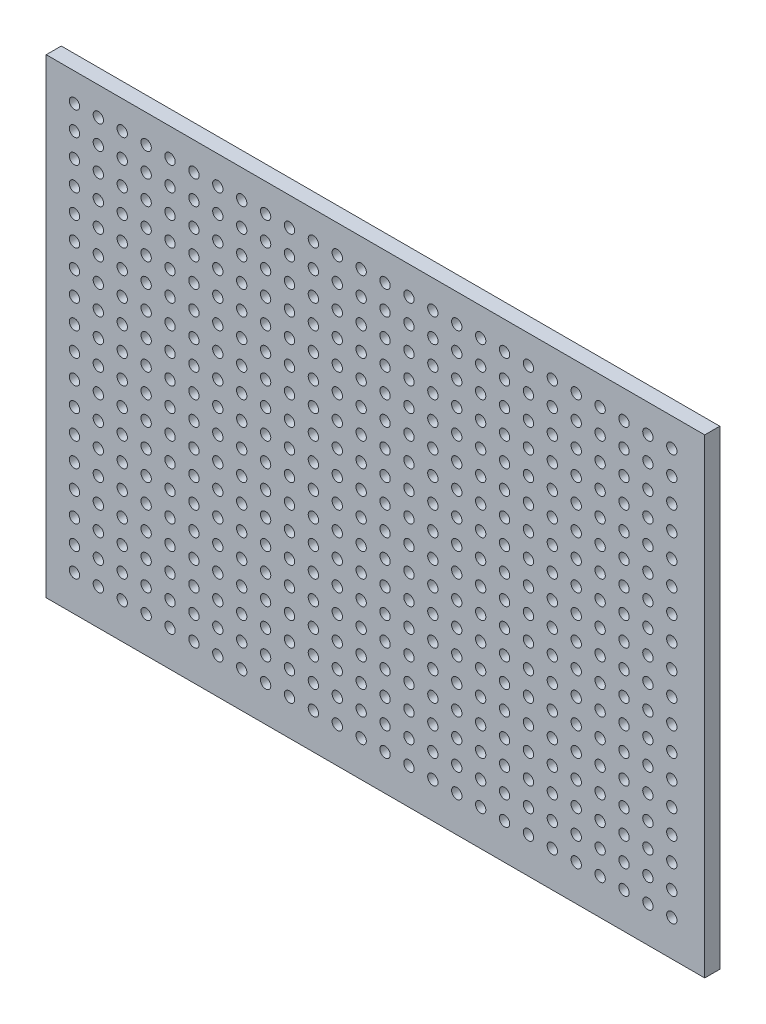
SolidWorks part; units mm, degrees
ref_plane "Front Plane" through (0, 0, 0) normal (0, 0, 1) x (1, 0, 0)
ref_plane "Top Plane" through (0, 0, 0) normal (0, 1, 0) x (1, 0, 0)
ref_plane "Right Plane" through (0, 0, 0) normal (1, 0, 0) x (0, 0, -1)
sketch "Sketch1" plane through (0, 0, 0) normal (0, 0, 1) x (1, 0, 0)
  line L1 (-35, -25) -> (35, -25)
  line L2 (-35, -25) -> (-35, 25)
  line L3 (-35, 25) -> (35, 25)
  line L4 (35, -25) -> (35, 25)
  line L5 (-35, -25) -> (35, 25) construction
  line L6 (-35, 25) -> (35, -25) construction
  point P0 (0, 0)
  dimension "D1" = 50
  dimension "D2" = 70
extrude "Boss-Extrude1" add sketch "Sketch1" along normal blind 1.6
sketch "Sketch2" plane through (0, 0, 1.6) normal (0, 0, 1) x (1, 0, 0)
  line L0 (-35, 25) -> (-35, -25) construction
  line L1 (35, 25) -> (-35, 25) construction
  line L2 (-32, 22) -> (-29.46, 22) construction
  line L3 (-32, 22) -> (-32, 19.46) construction
  circle A0 centre (-32, 22) radius 0.55
  circle A1 centre (-29.46, 22) radius 0.55
  circle A2 centre (-26.92, 22) radius 0.55
  circle A3 centre (-24.38, 22) radius 0.55
  circle A4 centre (-21.84, 22) radius 0.55
  circle A5 centre (-19.3, 22) radius 0.55
  circle A6 centre (-16.76, 22) radius 0.55
  circle A7 centre (-14.22, 22) radius 0.55
  circle A8 centre (-11.68, 22) radius 0.55
  circle A9 centre (-9.14, 22) radius 0.55
  circle A10 centre (-6.6, 22) radius 0.55
  circle A11 centre (-4.06, 22) radius 0.55
  circle A12 centre (-1.52, 22) radius 0.55
  circle A13 centre (1.02, 22) radius 0.55
  circle A14 centre (3.56, 22) radius 0.55
  circle A15 centre (6.1, 22) radius 0.55
  circle A16 centre (8.64, 22) radius 0.55
  circle A17 centre (11.18, 22) radius 0.55
  circle A18 centre (13.72, 22) radius 0.55
  circle A19 centre (16.26, 22) radius 0.55
  circle A20 centre (18.8, 22) radius 0.55
  circle A21 centre (21.34, 22) radius 0.55
  circle A22 centre (23.88, 22) radius 0.55
  circle A23 centre (26.42, 22) radius 0.55
  circle A24 centre (28.96, 22) radius 0.55
  circle A25 centre (31.5, 22) radius 0.55
  circle A26 centre (-29.46, 19.46) radius 0.55
  circle A27 centre (-26.92, 19.46) radius 0.55
  circle A28 centre (-24.38, 19.46) radius 0.55
  circle A29 centre (-21.84, 19.46) radius 0.55
  circle A30 centre (-19.3, 19.46) radius 0.55
  circle A31 centre (-16.76, 19.46) radius 0.55
  circle A32 centre (-14.22, 19.46) radius 0.55
  circle A33 centre (-11.68, 19.46) radius 0.55
  circle A34 centre (-9.14, 19.46) radius 0.55
  circle A35 centre (-6.6, 19.46) radius 0.55
  circle A36 centre (-4.06, 19.46) radius 0.55
  circle A37 centre (-1.52, 19.46) radius 0.55
  circle A38 centre (1.02, 19.46) radius 0.55
  circle A39 centre (3.56, 19.46) radius 0.55
  circle A40 centre (6.1, 19.46) radius 0.55
  circle A41 centre (8.64, 19.46) radius 0.55
  circle A42 centre (11.18, 19.46) radius 0.55
  circle A43 centre (13.72, 19.46) radius 0.55
  circle A44 centre (16.26, 19.46) radius 0.55
  circle A45 centre (18.8, 19.46) radius 0.55
  circle A46 centre (21.34, 19.46) radius 0.55
  circle A47 centre (23.88, 19.46) radius 0.55
  circle A48 centre (26.42, 19.46) radius 0.55
  circle A49 centre (28.96, 19.46) radius 0.55
  circle A50 centre (31.5, 19.46) radius 0.55
  circle A51 centre (-29.46, 16.92) radius 0.55
  circle A52 centre (-26.92, 16.92) radius 0.55
  circle A53 centre (-24.38, 16.92) radius 0.55
  circle A54 centre (-21.84, 16.92) radius 0.55
  circle A55 centre (-19.3, 16.92) radius 0.55
  circle A56 centre (-16.76, 16.92) radius 0.55
  circle A57 centre (-14.22, 16.92) radius 0.55
  circle A58 centre (-11.68, 16.92) radius 0.55
  circle A59 centre (-9.14, 16.92) radius 0.55
  circle A60 centre (-6.6, 16.92) radius 0.55
  circle A61 centre (-4.06, 16.92) radius 0.55
  circle A62 centre (-1.52, 16.92) radius 0.55
  circle A63 centre (1.02, 16.92) radius 0.55
  circle A64 centre (3.56, 16.92) radius 0.55
  circle A65 centre (6.1, 16.92) radius 0.55
  circle A66 centre (8.64, 16.92) radius 0.55
  circle A67 centre (11.18, 16.92) radius 0.55
  circle A68 centre (13.72, 16.92) radius 0.55
  circle A69 centre (16.26, 16.92) radius 0.55
  circle A70 centre (18.8, 16.92) radius 0.55
  circle A71 centre (21.34, 16.92) radius 0.55
  circle A72 centre (23.88, 16.92) radius 0.55
  circle A73 centre (26.42, 16.92) radius 0.55
  circle A74 centre (28.96, 16.92) radius 0.55
  circle A75 centre (31.5, 16.92) radius 0.55
  circle A76 centre (-29.46, 14.38) radius 0.55
  circle A77 centre (-26.92, 14.38) radius 0.55
  circle A78 centre (-24.38, 14.38) radius 0.55
  circle A79 centre (-21.84, 14.38) radius 0.55
  circle A80 centre (-19.3, 14.38) radius 0.55
  circle A81 centre (-16.76, 14.38) radius 0.55
  circle A82 centre (-14.22, 14.38) radius 0.55
  circle A83 centre (-11.68, 14.38) radius 0.55
  circle A84 centre (-9.14, 14.38) radius 0.55
  circle A85 centre (-6.6, 14.38) radius 0.55
  circle A86 centre (-4.06, 14.38) radius 0.55
  circle A87 centre (-1.52, 14.38) radius 0.55
  circle A88 centre (1.02, 14.38) radius 0.55
  circle A89 centre (3.56, 14.38) radius 0.55
  circle A90 centre (6.1, 14.38) radius 0.55
  circle A91 centre (8.64, 14.38) radius 0.55
  circle A92 centre (11.18, 14.38) radius 0.55
  circle A93 centre (13.72, 14.38) radius 0.55
  circle A94 centre (16.26, 14.38) radius 0.55
  circle A95 centre (18.8, 14.38) radius 0.55
  circle A96 centre (21.34, 14.38) radius 0.55
  circle A97 centre (23.88, 14.38) radius 0.55
  circle A98 centre (26.42, 14.38) radius 0.55
  circle A99 centre (28.96, 14.38) radius 0.55
  circle A100 centre (31.5, 14.38) radius 0.55
  circle A101 centre (-29.46, 11.84) radius 0.55
  circle A102 centre (-26.92, 11.84) radius 0.55
  circle A103 centre (-24.38, 11.84) radius 0.55
  circle A104 centre (-21.84, 11.84) radius 0.55
  circle A105 centre (-19.3, 11.84) radius 0.55
  circle A106 centre (-16.76, 11.84) radius 0.55
  circle A107 centre (-14.22, 11.84) radius 0.55
  circle A108 centre (-11.68, 11.84) radius 0.55
  circle A109 centre (-9.14, 11.84) radius 0.55
  circle A110 centre (-6.6, 11.84) radius 0.55
  circle A111 centre (-4.06, 11.84) radius 0.55
  circle A112 centre (-1.52, 11.84) radius 0.55
  circle A113 centre (1.02, 11.84) radius 0.55
  circle A114 centre (3.56, 11.84) radius 0.55
  circle A115 centre (6.1, 11.84) radius 0.55
  circle A116 centre (8.64, 11.84) radius 0.55
  circle A117 centre (11.18, 11.84) radius 0.55
  circle A118 centre (13.72, 11.84) radius 0.55
  circle A119 centre (16.26, 11.84) radius 0.55
  circle A120 centre (18.8, 11.84) radius 0.55
  circle A121 centre (21.34, 11.84) radius 0.55
  circle A122 centre (23.88, 11.84) radius 0.55
  circle A123 centre (26.42, 11.84) radius 0.55
  circle A124 centre (28.96, 11.84) radius 0.55
  circle A125 centre (31.5, 11.84) radius 0.55
  circle A126 centre (-29.46, 9.3) radius 0.55
  circle A127 centre (-26.92, 9.3) radius 0.55
  circle A128 centre (-24.38, 9.3) radius 0.55
  circle A129 centre (-21.84, 9.3) radius 0.55
  circle A130 centre (-19.3, 9.3) radius 0.55
  circle A131 centre (-16.76, 9.3) radius 0.55
  circle A132 centre (-14.22, 9.3) radius 0.55
  circle A133 centre (-11.68, 9.3) radius 0.55
  circle A134 centre (-9.14, 9.3) radius 0.55
  circle A135 centre (-6.6, 9.3) radius 0.55
  circle A136 centre (-4.06, 9.3) radius 0.55
  circle A137 centre (-1.52, 9.3) radius 0.55
  circle A138 centre (1.02, 9.3) radius 0.55
  circle A139 centre (3.56, 9.3) radius 0.55
  circle A140 centre (6.1, 9.3) radius 0.55
  circle A141 centre (8.64, 9.3) radius 0.55
  circle A142 centre (11.18, 9.3) radius 0.55
  circle A143 centre (13.72, 9.3) radius 0.55
  circle A144 centre (16.26, 9.3) radius 0.55
  circle A145 centre (18.8, 9.3) radius 0.55
  circle A146 centre (21.34, 9.3) radius 0.55
  circle A147 centre (23.88, 9.3) radius 0.55
  circle A148 centre (26.42, 9.3) radius 0.55
  circle A149 centre (28.96, 9.3) radius 0.55
  circle A150 centre (31.5, 9.3) radius 0.55
  circle A151 centre (-29.46, 6.76) radius 0.55
  circle A152 centre (-26.92, 6.76) radius 0.55
  circle A153 centre (-24.38, 6.76) radius 0.55
  circle A154 centre (-21.84, 6.76) radius 0.55
  circle A155 centre (-19.3, 6.76) radius 0.55
  circle A156 centre (-16.76, 6.76) radius 0.55
  circle A157 centre (-14.22, 6.76) radius 0.55
  circle A158 centre (-11.68, 6.76) radius 0.55
  circle A159 centre (-9.14, 6.76) radius 0.55
  circle A160 centre (-6.6, 6.76) radius 0.55
  circle A161 centre (-4.06, 6.76) radius 0.55
  circle A162 centre (-1.52, 6.76) radius 0.55
  circle A163 centre (1.02, 6.76) radius 0.55
  circle A164 centre (3.56, 6.76) radius 0.55
  circle A165 centre (6.1, 6.76) radius 0.55
  circle A166 centre (8.64, 6.76) radius 0.55
  circle A167 centre (11.18, 6.76) radius 0.55
  circle A168 centre (13.72, 6.76) radius 0.55
  circle A169 centre (16.26, 6.76) radius 0.55
  circle A170 centre (18.8, 6.76) radius 0.55
  circle A171 centre (21.34, 6.76) radius 0.55
  circle A172 centre (23.88, 6.76) radius 0.55
  circle A173 centre (26.42, 6.76) radius 0.55
  circle A174 centre (28.96, 6.76) radius 0.55
  circle A175 centre (31.5, 6.76) radius 0.55
  circle A176 centre (-29.46, 4.22) radius 0.55
  circle A177 centre (-26.92, 4.22) radius 0.55
  circle A178 centre (-24.38, 4.22) radius 0.55
  circle A179 centre (-21.84, 4.22) radius 0.55
  circle A180 centre (-19.3, 4.22) radius 0.55
  circle A181 centre (-16.76, 4.22) radius 0.55
  circle A182 centre (-14.22, 4.22) radius 0.55
  circle A183 centre (-11.68, 4.22) radius 0.55
  circle A184 centre (-9.14, 4.22) radius 0.55
  circle A185 centre (-6.6, 4.22) radius 0.55
  circle A186 centre (-4.06, 4.22) radius 0.55
  circle A187 centre (-1.52, 4.22) radius 0.55
  circle A188 centre (1.02, 4.22) radius 0.55
  circle A189 centre (3.56, 4.22) radius 0.55
  circle A190 centre (6.1, 4.22) radius 0.55
  circle A191 centre (8.64, 4.22) radius 0.55
  circle A192 centre (11.18, 4.22) radius 0.55
  circle A193 centre (13.72, 4.22) radius 0.55
  circle A194 centre (16.26, 4.22) radius 0.55
  circle A195 centre (18.8, 4.22) radius 0.55
  circle A196 centre (21.34, 4.22) radius 0.55
  circle A197 centre (23.88, 4.22) radius 0.55
  circle A198 centre (26.42, 4.22) radius 0.55
  circle A199 centre (28.96, 4.22) radius 0.55
  circle A200 centre (31.5, 4.22) radius 0.55
  circle A201 centre (-29.46, 1.68) radius 0.55
  circle A202 centre (-26.92, 1.68) radius 0.55
  circle A203 centre (-24.38, 1.68) radius 0.55
  circle A204 centre (-21.84, 1.68) radius 0.55
  circle A205 centre (-19.3, 1.68) radius 0.55
  circle A206 centre (-16.76, 1.68) radius 0.55
  circle A207 centre (-14.22, 1.68) radius 0.55
  circle A208 centre (-11.68, 1.68) radius 0.55
  circle A209 centre (-9.14, 1.68) radius 0.55
  circle A210 centre (-6.6, 1.68) radius 0.55
  circle A211 centre (-4.06, 1.68) radius 0.55
  circle A212 centre (-1.52, 1.68) radius 0.55
  circle A213 centre (1.02, 1.68) radius 0.55
  circle A214 centre (3.56, 1.68) radius 0.55
  circle A215 centre (6.1, 1.68) radius 0.55
  circle A216 centre (8.64, 1.68) radius 0.55
  circle A217 centre (11.18, 1.68) radius 0.55
  circle A218 centre (13.72, 1.68) radius 0.55
  circle A219 centre (16.26, 1.68) radius 0.55
  circle A220 centre (18.8, 1.68) radius 0.55
  circle A221 centre (21.34, 1.68) radius 0.55
  circle A222 centre (23.88, 1.68) radius 0.55
  circle A223 centre (26.42, 1.68) radius 0.55
  circle A224 centre (28.96, 1.68) radius 0.55
  circle A225 centre (31.5, 1.68) radius 0.55
  circle A226 centre (-29.46, -0.86) radius 0.55
  circle A227 centre (-26.92, -0.86) radius 0.55
  circle A228 centre (-24.38, -0.86) radius 0.55
  circle A229 centre (-21.84, -0.86) radius 0.55
  circle A230 centre (-19.3, -0.86) radius 0.55
  circle A231 centre (-16.76, -0.86) radius 0.55
  circle A232 centre (-14.22, -0.86) radius 0.55
  circle A233 centre (-11.68, -0.86) radius 0.55
  circle A234 centre (-9.14, -0.86) radius 0.55
  circle A235 centre (-6.6, -0.86) radius 0.55
  circle A236 centre (-4.06, -0.86) radius 0.55
  circle A237 centre (-1.52, -0.86) radius 0.55
  circle A238 centre (1.02, -0.86) radius 0.55
  circle A239 centre (3.56, -0.86) radius 0.55
  circle A240 centre (6.1, -0.86) radius 0.55
  circle A241 centre (8.64, -0.86) radius 0.55
  circle A242 centre (11.18, -0.86) radius 0.55
  circle A243 centre (13.72, -0.86) radius 0.55
  circle A244 centre (16.26, -0.86) radius 0.55
  circle A245 centre (18.8, -0.86) radius 0.55
  circle A246 centre (21.34, -0.86) radius 0.55
  circle A247 centre (23.88, -0.86) radius 0.55
  circle A248 centre (26.42, -0.86) radius 0.55
  circle A249 centre (28.96, -0.86) radius 0.55
  circle A250 centre (31.5, -0.86) radius 0.55
  circle A251 centre (-29.46, -3.4) radius 0.55
  circle A252 centre (-26.92, -3.4) radius 0.55
  circle A253 centre (-24.38, -3.4) radius 0.55
  circle A254 centre (-21.84, -3.4) radius 0.55
  circle A255 centre (-19.3, -3.4) radius 0.55
  circle A256 centre (-16.76, -3.4) radius 0.55
  circle A257 centre (-14.22, -3.4) radius 0.55
  circle A258 centre (-11.68, -3.4) radius 0.55
  circle A259 centre (-9.14, -3.4) radius 0.55
  circle A260 centre (-6.6, -3.4) radius 0.55
  circle A261 centre (-4.06, -3.4) radius 0.55
  circle A262 centre (-1.52, -3.4) radius 0.55
  circle A263 centre (1.02, -3.4) radius 0.55
  circle A264 centre (3.56, -3.4) radius 0.55
  circle A265 centre (6.1, -3.4) radius 0.55
  circle A266 centre (8.64, -3.4) radius 0.55
  circle A267 centre (11.18, -3.4) radius 0.55
  circle A268 centre (13.72, -3.4) radius 0.55
  circle A269 centre (16.26, -3.4) radius 0.55
  circle A270 centre (18.8, -3.4) radius 0.55
  circle A271 centre (21.34, -3.4) radius 0.55
  circle A272 centre (23.88, -3.4) radius 0.55
  circle A273 centre (26.42, -3.4) radius 0.55
  circle A274 centre (28.96, -3.4) radius 0.55
  circle A275 centre (31.5, -3.4) radius 0.55
  circle A276 centre (-29.46, -5.94) radius 0.55
  circle A277 centre (-26.92, -5.94) radius 0.55
  circle A278 centre (-24.38, -5.94) radius 0.55
  circle A279 centre (-21.84, -5.94) radius 0.55
  circle A280 centre (-19.3, -5.94) radius 0.55
  circle A281 centre (-16.76, -5.94) radius 0.55
  circle A282 centre (-14.22, -5.94) radius 0.55
  circle A283 centre (-11.68, -5.94) radius 0.55
  circle A284 centre (-9.14, -5.94) radius 0.55
  circle A285 centre (-6.6, -5.94) radius 0.55
  circle A286 centre (-4.06, -5.94) radius 0.55
  circle A287 centre (-1.52, -5.94) radius 0.55
  circle A288 centre (1.02, -5.94) radius 0.55
  circle A289 centre (3.56, -5.94) radius 0.55
  circle A290 centre (6.1, -5.94) radius 0.55
  circle A291 centre (8.64, -5.94) radius 0.55
  circle A292 centre (11.18, -5.94) radius 0.55
  circle A293 centre (13.72, -5.94) radius 0.55
  circle A294 centre (16.26, -5.94) radius 0.55
  circle A295 centre (18.8, -5.94) radius 0.55
  circle A296 centre (21.34, -5.94) radius 0.55
  circle A297 centre (23.88, -5.94) radius 0.55
  circle A298 centre (26.42, -5.94) radius 0.55
  circle A299 centre (28.96, -5.94) radius 0.55
  circle A300 centre (31.5, -5.94) radius 0.55
  circle A301 centre (-29.46, -8.48) radius 0.55
  circle A302 centre (-26.92, -8.48) radius 0.55
  circle A303 centre (-24.38, -8.48) radius 0.55
  circle A304 centre (-21.84, -8.48) radius 0.55
  circle A305 centre (-19.3, -8.48) radius 0.55
  circle A306 centre (-16.76, -8.48) radius 0.55
  circle A307 centre (-14.22, -8.48) radius 0.55
  circle A308 centre (-11.68, -8.48) radius 0.55
  circle A309 centre (-9.14, -8.48) radius 0.55
  circle A310 centre (-6.6, -8.48) radius 0.55
  circle A311 centre (-4.06, -8.48) radius 0.55
  circle A312 centre (-1.52, -8.48) radius 0.55
  circle A313 centre (1.02, -8.48) radius 0.55
  circle A314 centre (3.56, -8.48) radius 0.55
  circle A315 centre (6.1, -8.48) radius 0.55
  circle A316 centre (8.64, -8.48) radius 0.55
  circle A317 centre (11.18, -8.48) radius 0.55
  circle A318 centre (13.72, -8.48) radius 0.55
  circle A319 centre (16.26, -8.48) radius 0.55
  circle A320 centre (18.8, -8.48) radius 0.55
  circle A321 centre (21.34, -8.48) radius 0.55
  circle A322 centre (23.88, -8.48) radius 0.55
  circle A323 centre (26.42, -8.48) radius 0.55
  circle A324 centre (28.96, -8.48) radius 0.55
  circle A325 centre (31.5, -8.48) radius 0.55
  circle A326 centre (-29.46, -11.02) radius 0.55
  circle A327 centre (-26.92, -11.02) radius 0.55
  circle A328 centre (-24.38, -11.02) radius 0.55
  circle A329 centre (-21.84, -11.02) radius 0.55
  circle A330 centre (-19.3, -11.02) radius 0.55
  circle A331 centre (-16.76, -11.02) radius 0.55
  circle A332 centre (-14.22, -11.02) radius 0.55
  circle A333 centre (-11.68, -11.02) radius 0.55
  circle A334 centre (-9.14, -11.02) radius 0.55
  circle A335 centre (-6.6, -11.02) radius 0.55
  circle A336 centre (-4.06, -11.02) radius 0.55
  circle A337 centre (-1.52, -11.02) radius 0.55
  circle A338 centre (1.02, -11.02) radius 0.55
  circle A339 centre (3.56, -11.02) radius 0.55
  circle A340 centre (6.1, -11.02) radius 0.55
  circle A341 centre (8.64, -11.02) radius 0.55
  circle A342 centre (11.18, -11.02) radius 0.55
  circle A343 centre (13.72, -11.02) radius 0.55
  circle A344 centre (16.26, -11.02) radius 0.55
  circle A345 centre (18.8, -11.02) radius 0.55
  circle A346 centre (21.34, -11.02) radius 0.55
  circle A347 centre (23.88, -11.02) radius 0.55
  circle A348 centre (26.42, -11.02) radius 0.55
  circle A349 centre (28.96, -11.02) radius 0.55
  circle A350 centre (31.5, -11.02) radius 0.55
  circle A351 centre (-29.46, -13.56) radius 0.55
  circle A352 centre (-26.92, -13.56) radius 0.55
  circle A353 centre (-24.38, -13.56) radius 0.55
  circle A354 centre (-21.84, -13.56) radius 0.55
  circle A355 centre (-19.3, -13.56) radius 0.55
  circle A356 centre (-16.76, -13.56) radius 0.55
  circle A357 centre (-14.22, -13.56) radius 0.55
  circle A358 centre (-11.68, -13.56) radius 0.55
  circle A359 centre (-9.14, -13.56) radius 0.55
  circle A360 centre (-6.6, -13.56) radius 0.55
  circle A361 centre (-4.06, -13.56) radius 0.55
  circle A362 centre (-1.52, -13.56) radius 0.55
  circle A363 centre (1.02, -13.56) radius 0.55
  circle A364 centre (3.56, -13.56) radius 0.55
  circle A365 centre (6.1, -13.56) radius 0.55
  circle A366 centre (8.64, -13.56) radius 0.55
  circle A367 centre (11.18, -13.56) radius 0.55
  circle A368 centre (13.72, -13.56) radius 0.55
  circle A369 centre (16.26, -13.56) radius 0.55
  circle A370 centre (18.8, -13.56) radius 0.55
  circle A371 centre (21.34, -13.56) radius 0.55
  circle A372 centre (23.88, -13.56) radius 0.55
  circle A373 centre (26.42, -13.56) radius 0.55
  circle A374 centre (28.96, -13.56) radius 0.55
  circle A375 centre (31.5, -13.56) radius 0.55
  circle A376 centre (-29.46, -16.1) radius 0.55
  circle A377 centre (-26.92, -16.1) radius 0.55
  circle A378 centre (-24.38, -16.1) radius 0.55
  circle A379 centre (-21.84, -16.1) radius 0.55
  circle A380 centre (-19.3, -16.1) radius 0.55
  circle A381 centre (-16.76, -16.1) radius 0.55
  circle A382 centre (-14.22, -16.1) radius 0.55
  circle A383 centre (-11.68, -16.1) radius 0.55
  circle A384 centre (-9.14, -16.1) radius 0.55
  circle A385 centre (-6.6, -16.1) radius 0.55
  circle A386 centre (-4.06, -16.1) radius 0.55
  circle A387 centre (-1.52, -16.1) radius 0.55
  circle A388 centre (1.02, -16.1) radius 0.55
  circle A389 centre (3.56, -16.1) radius 0.55
  circle A390 centre (6.1, -16.1) radius 0.55
  circle A391 centre (8.64, -16.1) radius 0.55
  circle A392 centre (11.18, -16.1) radius 0.55
  circle A393 centre (13.72, -16.1) radius 0.55
  circle A394 centre (16.26, -16.1) radius 0.55
  circle A395 centre (18.8, -16.1) radius 0.55
  circle A396 centre (21.34, -16.1) radius 0.55
  circle A397 centre (23.88, -16.1) radius 0.55
  circle A398 centre (26.42, -16.1) radius 0.55
  circle A399 centre (28.96, -16.1) radius 0.55
  circle A400 centre (31.5, -16.1) radius 0.55
  circle A401 centre (-29.46, -18.64) radius 0.55
  circle A402 centre (-26.92, -18.64) radius 0.55
  circle A403 centre (-24.38, -18.64) radius 0.55
  circle A404 centre (-21.84, -18.64) radius 0.55
  circle A405 centre (-19.3, -18.64) radius 0.55
  circle A406 centre (-16.76, -18.64) radius 0.55
  circle A407 centre (-14.22, -18.64) radius 0.55
  circle A408 centre (-11.68, -18.64) radius 0.55
  circle A409 centre (-9.14, -18.64) radius 0.55
  circle A410 centre (-6.6, -18.64) radius 0.55
  circle A411 centre (-4.06, -18.64) radius 0.55
  circle A412 centre (-1.52, -18.64) radius 0.55
  circle A413 centre (1.02, -18.64) radius 0.55
  circle A414 centre (3.56, -18.64) radius 0.55
  circle A415 centre (6.1, -18.64) radius 0.55
  circle A416 centre (8.64, -18.64) radius 0.55
  circle A417 centre (11.18, -18.64) radius 0.55
  circle A418 centre (13.72, -18.64) radius 0.55
  circle A419 centre (16.26, -18.64) radius 0.55
  circle A420 centre (18.8, -18.64) radius 0.55
  circle A421 centre (21.34, -18.64) radius 0.55
  circle A422 centre (23.88, -18.64) radius 0.55
  circle A423 centre (26.42, -18.64) radius 0.55
  circle A424 centre (28.96, -18.64) radius 0.55
  circle A425 centre (31.5, -18.64) radius 0.55
  circle A426 centre (-29.46, -21.18) radius 0.55
  circle A427 centre (-26.92, -21.18) radius 0.55
  circle A428 centre (-24.38, -21.18) radius 0.55
  circle A429 centre (-21.84, -21.18) radius 0.55
  circle A430 centre (-19.3, -21.18) radius 0.55
  circle A431 centre (-16.76, -21.18) radius 0.55
  circle A432 centre (-14.22, -21.18) radius 0.55
  circle A433 centre (-11.68, -21.18) radius 0.55
  circle A434 centre (-9.14, -21.18) radius 0.55
  circle A435 centre (-6.6, -21.18) radius 0.55
  circle A436 centre (-4.06, -21.18) radius 0.55
  circle A437 centre (-1.52, -21.18) radius 0.55
  circle A438 centre (1.02, -21.18) radius 0.55
  circle A439 centre (3.56, -21.18) radius 0.55
  circle A440 centre (6.1, -21.18) radius 0.55
  circle A441 centre (8.64, -21.18) radius 0.55
  circle A442 centre (11.18, -21.18) radius 0.55
  circle A443 centre (13.72, -21.18) radius 0.55
  circle A444 centre (16.26, -21.18) radius 0.55
  circle A445 centre (18.8, -21.18) radius 0.55
  circle A446 centre (21.34, -21.18) radius 0.55
  circle A447 centre (23.88, -21.18) radius 0.55
  circle A448 centre (26.42, -21.18) radius 0.55
  circle A449 centre (28.96, -21.18) radius 0.55
  circle A450 centre (31.5, -21.18) radius 0.55
  circle A451 centre (-32, 19.46) radius 0.55
  circle A452 centre (-32, 16.92) radius 0.55
  circle A453 centre (-32, 14.38) radius 0.55
  circle A454 centre (-32, 11.84) radius 0.55
  circle A455 centre (-32, 9.3) radius 0.55
  circle A456 centre (-32, 6.76) radius 0.55
  circle A457 centre (-32, 4.22) radius 0.55
  circle A458 centre (-32, 1.68) radius 0.55
  circle A459 centre (-32, -0.86) radius 0.55
  circle A460 centre (-32, -3.4) radius 0.55
  circle A461 centre (-32, -5.94) radius 0.55
  circle A462 centre (-32, -8.48) radius 0.55
  circle A463 centre (-32, -11.02) radius 0.55
  circle A464 centre (-32, -13.56) radius 0.55
  circle A465 centre (-32, -16.1) radius 0.55
  circle A466 centre (-32, -18.64) radius 0.55
  circle A467 centre (-32, -21.18) radius 0.55
  dimension "D1" = 1.1
  dimension "D4" = 26
  dimension "D2" = 3
  dimension "D3" = 3
  dimension "D6" = 90
  dimension "D7" = 2.54
  dimension "D8" = 2.54
  dimension "D5" = 18
extrude "Cut-Extrude2" cut sketch "Sketch2" against normal through all
